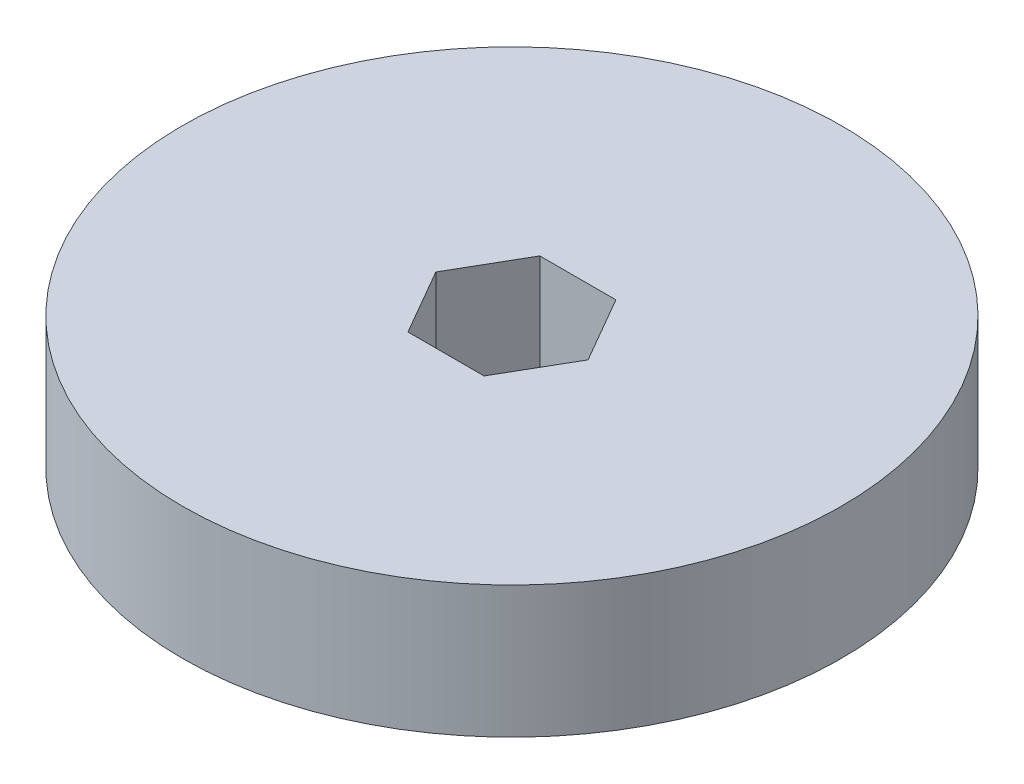
SolidWorks part; units mm, degrees
ref_plane "Front Plane" through (0, 0, 0) normal (0, 0, 1) x (1, 0, 0)
ref_plane "Top Plane" through (0, 0, 0) normal (0, 1, 0) x (1, 0, 0)
ref_plane "Right Plane" through (0, 0, 0) normal (1, 0, 0) x (0, 0, -1)
sketch "Sketch1" plane through (0, 0, 0) normal (0, 1, 0) x (1, 0, 0)
  line L1 (-7.3323, 0) -> (-3.6662, -6.35)
  line L2 (-3.6662, -6.35) -> (3.6662, -6.35)
  line L3 (3.6662, -6.35) -> (7.3323, 0)
  line L4 (7.3323, 0) -> (3.6662, 6.35)
  line L5 (3.6662, 6.35) -> (-3.6662, 6.35)
  line L6 (-3.6662, 6.35) -> (-7.3323, 0)
  circle A0 centre (0, 0) radius 31.75
  circle A1 centre (0, 0) radius 6.35 construction
  dimension "D1" = 63.5
  dimension "D2" = 12.7
extrude "Boss-Extrude1" add sketch "Sketch1" along normal blind 12.7
